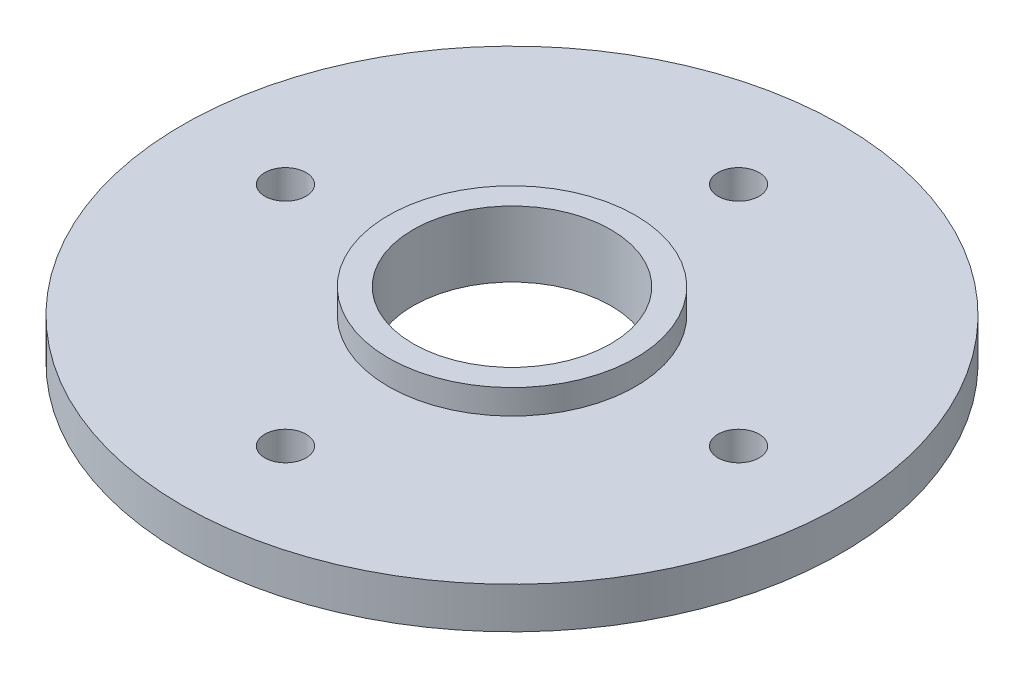
SolidWorks part; units mm, degrees
ref_plane "Front Plane" through (0, 0, 0) normal (0, 0, 1) x (1, 0, 0)
ref_plane "Top Plane" through (0, 0, 0) normal (0, 1, 0) x (1, 0, 0)
ref_plane "Right Plane" through (0, 0, 0) normal (1, 0, 0) x (0, 0, -1)
sketch "Sketch1" plane through (0, 0, 0) normal (0, 1, 0) x (1, 0, 0)
  circle A0 centre (0, 0) radius 40
  dimension "D1" = 80
extrude "Boss-Extrude1" add sketch "Sketch1" along normal blind 5
sketch "Sketch2" plane through (0, 5, 0) normal (0, 1, 0) x (1, 0, 0)
  circle A0 centre (0, 0) radius 12
  circle A1 centre (0, 0) radius 15
  dimension "D1" = 24
  dimension "D2" = 30
extrude "Boss-Extrude2" add sketch "Sketch2" along normal blind 3
sketch "Sketch3" plane through (0, 5, 0) normal (0, 1, 0) x (1, 0, 0)
  circle A0 centre (0, 0) radius 12
extrude "Cut-Extrude1" cut sketch "Sketch3" against normal through all
sketch "Sketch4" plane through (0, 5, 0) normal (0, 1, 0) x (1, 0, 0)
  line L0 (0, 0) -> (0, 27.5) construction
  circle A0 centre (0, 0) radius 27.5
  dimension "D1" = 55
hole_wizard "Ø5.0mm Dowel Hole1" positions "3DSketch2" profile "Sketch5" hole size "Ø5.0" standard "ANSI Metric" end condition through all
sketch3d "3DSketch2"
  point P0 (0, 5, -27.5)
sketch "Sketch5" plane through (0, 5, -27.5) normal (1, 0, 0) x (0, 0, 1)
  line L0 (0, 0) -> (0, 5)
  line L1 (0, 5) -> (2.5, 5)
  line L2 (2.5, 5) -> (2.5, 0)
  line L5 (2.5, 0) -> (0, 0)
  line L11 (0, -6.35) -> (0, 107.95) construction
  dimension "Thru Hole Dia." = 5
  dimension "Thru Hole Depth" = 5
pattern_circular "CirPattern1" count 4 over 360 about axis through (0, 0, 0) along (0, 1, 0) of "Ø5.0mm Dowel Hole1"
